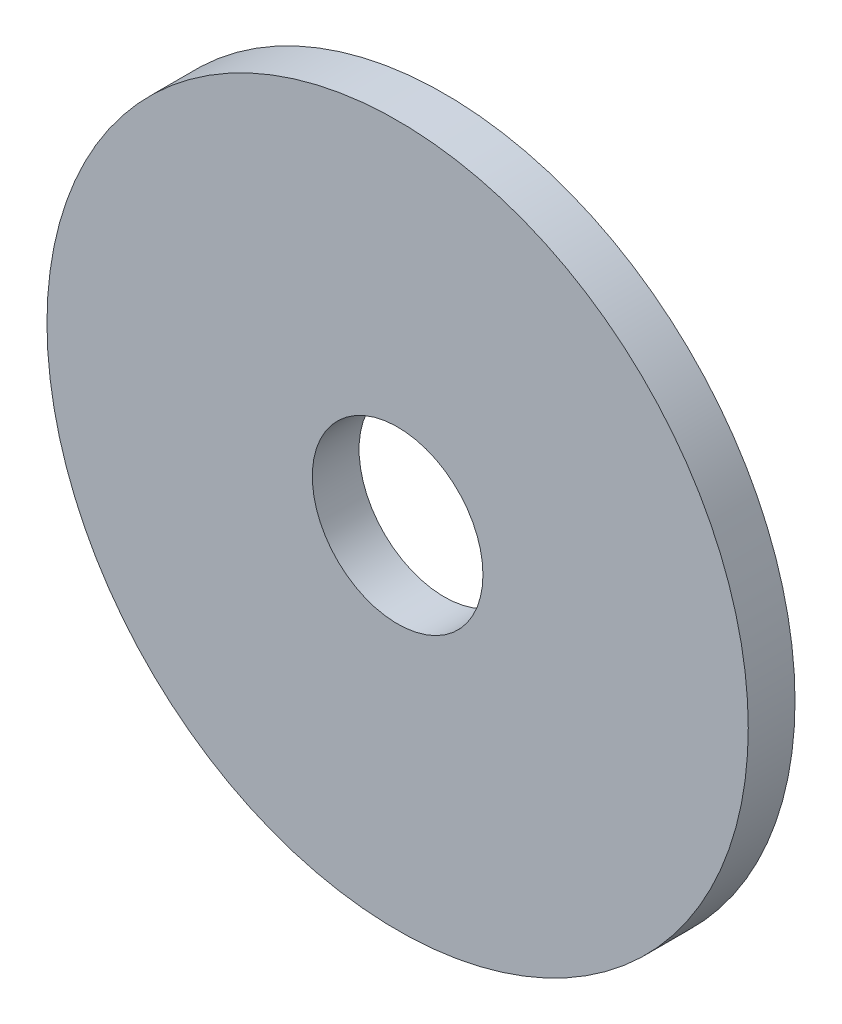
SolidWorks part; units mm, degrees
material "ABS"
ref_plane "Front Plane" through (0, 0, 0) normal (0, 0, 1) x (1, 0, 0)
ref_plane "Top Plane" through (0, 0, 0) normal (0, 1, 0) x (1, 0, 0)
ref_plane "Right Plane" through (0, 0, 0) normal (1, 0, 0) x (0, 0, -1)
sketch "Croquis1" plane through (0, 0, 0) normal (0, 0, 1) x (1, 0, 0)
  circle A0 centre (0, 0) radius 15
  circle A1 centre (0, 0) radius 3.65
  dimension "D1" = 30
  dimension "D2" = 7.3
extrude "Saliente-Extruir1" add sketch "Croquis1" along normal mid plane 2
